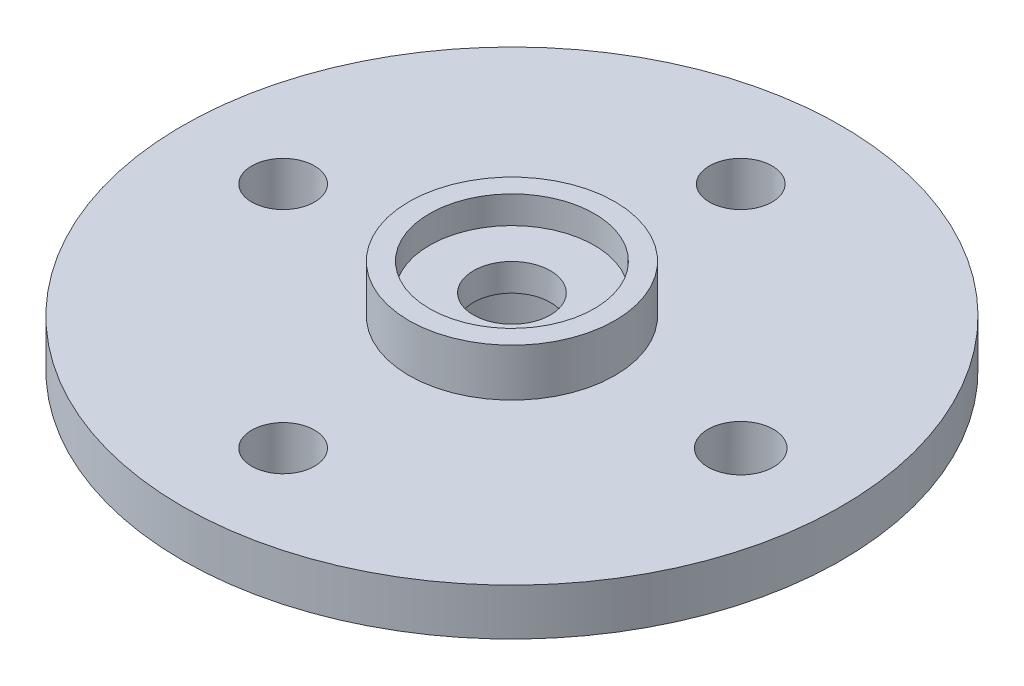
SolidWorks part; units mm, degrees
material "PC High Viscosity"
ref_plane "Front Plane" through (0, 0, 0) normal (0, 0, 1) x (1, 0, 0)
ref_plane "Top Plane" through (0, 0, 0) normal (0, 1, 0) x (1, 0, 0)
ref_plane "Right Plane" through (0, 0, 0) normal (1, 0, 0) x (0, 0, -1)
sketch "Sketch1" plane through (0, 0, 0) normal (0, 0, 1) x (1, 0, 0)
  line L0 (0, 0) -> (0, -3.2676) construction
  line L1 (0, -55) -> (0, 55) construction
  line L2 (55, 0) -> (-55, 0) construction
  line L3 (-12, 0) -> (-3.75, 0)
  line L4 (-12, 0) -> (-12, -1.7006)
  line L5 (-12, -1.7006) -> (-4.45, -1.7006)
  line L6 (-1.4, 1.7324) -> (-1.4, -3.2676)
  line L8 (-4.45, -1.7006) -> (-4.45, -3.2676)
  line L9 (-4.45, -3.2676) -> (-1.4, -3.2676)
  line L10 (-3.75, 1.7324) -> (-1.4, 1.7324)
  line L11 (-3.75, 1.7324) -> (-3.75, 0)
  dimension "D1" = 8.9
  dimension "D2" = 1.567
  dimension "D3" = 3.2676
  dimension "D4" = 24
  dimension "D5" = 2.8
  dimension "D6" = 7.5
  dimension "D7" = 5
revolve "Revolve1" add sketch "Sketch1" angle 360 about L0
sketch "Sketch4" plane through (0, 1.7324, 0) normal (0, 1, 0) x (-1, 0, 0)
  circle A0 centre (0, 0) radius 3
  dimension "D1" = 6
extrude "Cut-Extrude1" cut sketch "Sketch4" against normal blind 1
sketch "Sketch5" plane through (0, -3.2676, 0) normal (0, -1, 0) x (1, 0, 0)
  circle A0 centre (0, 0) radius 3
  dimension "D1" = 6
extrude "Cut-Extrude2" cut sketch "Sketch5" against normal blind 3
sketch "Sketch6" plane through (0, 0, 0) normal (0, 1, 0) x (1, 0, 0)
  circle A0 centre (0, 8.3312) radius 1.143
  circle A1 centre (-8.3312, 0) radius 1.143
  circle A2 centre (0, -8.3312) radius 1.143
  circle A3 centre (8.3312, 0) radius 1.1938
  dimension "D1" = 2.286
  dimension "D2" = 2.3876
  dimension "D3" = 2.286
  dimension "D4" = 2.286
  dimension "D5" = 8.3312
  dimension "D6" = 8.3312
  dimension "D7" = 8.3312
  dimension "D8" = 8.3312
extrude "Cut-Extrude3" cut sketch "Sketch6" against normal up to next
